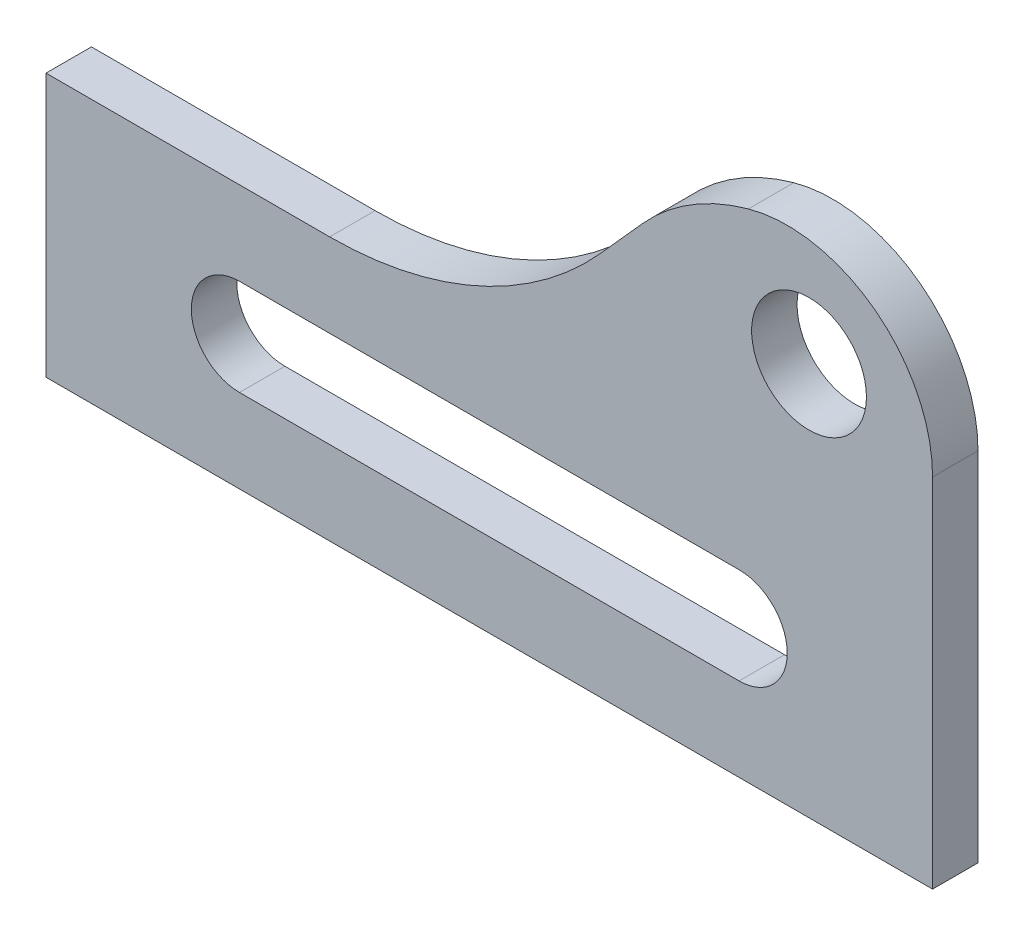
SolidWorks part; units mm, degrees
material "Balsa"
ref_plane "Front Plane" through (0, 0, 0) normal (0, 0, 1) x (1, 0, 0)
ref_plane "Top Plane" through (0, 0, 0) normal (0, 1, 0) x (1, 0, 0)
ref_plane "Right Plane" through (0, 0, 0) normal (1, 0, 0) x (0, 0, -1)
sketch "Sketch1" plane through (0, 0, 0) normal (0, 0, 1) x (1, 0, 0)
  line L0 (1.5875, 9.2075) -> (0, 9.2075) construction
  line L1 (0, 0) -> (30.988, 0)
  line L2 (0, 0) -> (0, 9.2075)
  line L3 (0, 9.2075) -> (30.988, 9.2075)
  line L4 (30.988, 0) -> (30.988, 9.2075)
  line L5 (30.988, 0) -> (30.988, 6.4214) construction
extrude "Boss-Extrude1" add sketch "Sketch1" along normal blind 1.5875
sketch "Sketch2" plane through (0, 0, 1.5875) normal (0, 0, 1) x (1, 0, 0)
  line L0 (30.988, 9.2075) -> (30.988, 16.3124)
  line L1 (20.8434, 15.0717) -> (15.5881, 9.2075)
  line L2 (30.988, 9.2075) -> (0, 9.2075) construction
  circle A0 centre (26.67, 13.7423) radius 2.0066 construction
  circle A1 centre (26.67, 13.7423) radius 2.0066
  arc A2 (34.29, 10.0339) -> (26.67, 17.6539) centre (26.67, 10.0339) ccw construction
  arc A3 (30.988, 16.3124) -> (20.8434, 15.0717) centre (26.6253, 9.8901) ccw
  arc A4 (26.67, 17.6539) -> (20.8434, 15.0717) centre (26.67, 9.7893) ccw construction
  line M4 (30.988, 9.2075) -> (0, 9.2075)
extrude "Boss-Extrude2" add sketch "Sketch2" against normal up to surface (1.5875 mm away) contours L0 A3 L1 A1 M4 up to face at (15.494, 4.6038, 0)
fillet "Fillet1" radius 12.7 1 edges
fillet "Fillet2" radius 5.08 1 edges at (30.988, 16.3124, 0.7937)
sketch "Sketch3" plane through (0, 0, 1.5875) normal (0, 0, 1) x (1, 0, 0)
  line L0 (6.7628, 4.6038) -> (24.2252, 4.6038) construction
  line L1 (6.7628, 6.2865) -> (24.2252, 6.2865)
  line L2 (6.7628, 2.921) -> (24.2252, 2.921)
  line L4 (9.9159, 9.2075) -> (0, 9.2075) construction
  line L5 (5.08, 4.6038) -> (5.08, 16.8213) construction
  line L7 (15.494, 0) -> (15.494, 21.2471) construction
  line L8 (0, 0) -> (30.988, 0) construction
  line L9 (0, 4.6038) -> (46.6173, 4.6038) construction
  line L10 (0, 9.2075) -> (0, 0) construction
  arc A0 (6.7628, 6.2865) -> (6.7628, 2.921) centre (6.7628, 4.6038) ccw
  arc A1 (24.2252, 2.921) -> (24.2252, 6.2865) centre (24.2252, 4.6038) ccw
  point P2 (15.494, 4.6038)
  dimension "D1" = 2.921
  dimension "D2" = 5.08
extrude "Cut-Extrude1" cut sketch "Sketch3" against normal through all
